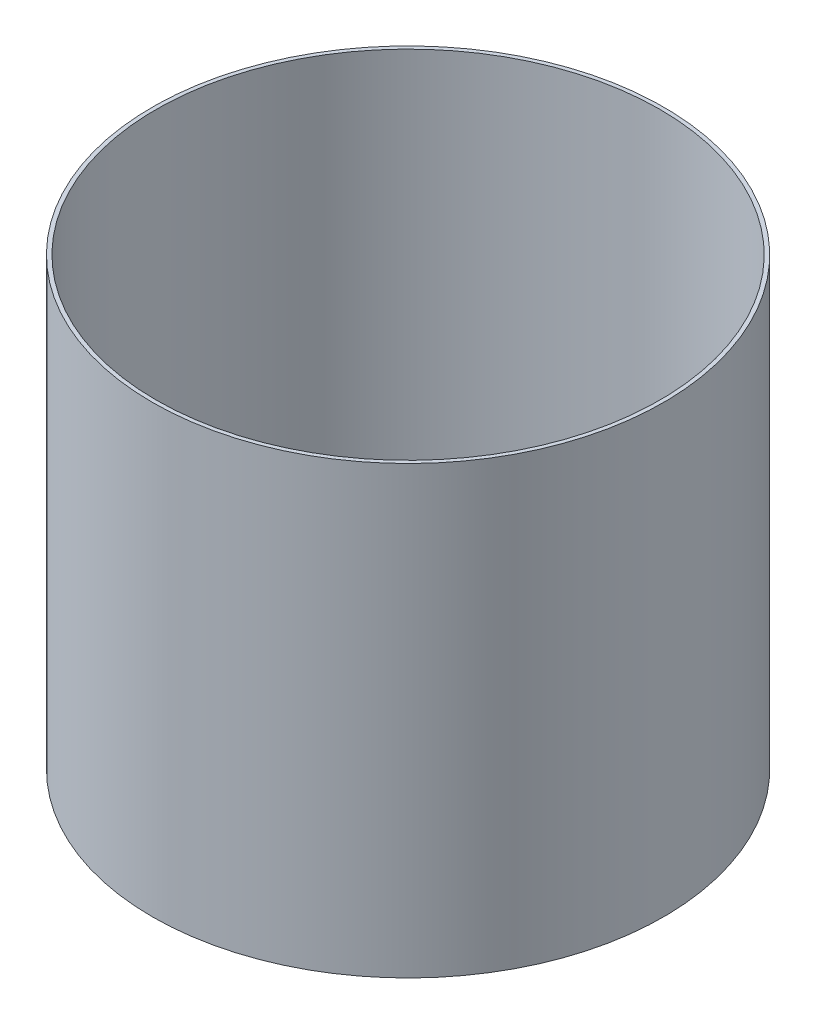
SolidWorks part; units mm, degrees
ref_plane "Front Plane" through (0, 0, 0) normal (0, 0, 1) x (1, 0, 0)
ref_plane "Top Plane" through (0, 0, 0) normal (0, 1, 0) x (1, 0, 0)
ref_plane "Right Plane" through (0, 0, 0) normal (1, 0, 0) x (0, 0, -1)
sketch "Sketch1" plane through (0, 0, 0) normal (0, 1, 0) x (1, 0, 0)
  circle A0 centre (0, 0) radius 335.28
extrude "Boss-Extrude2" add sketch "Sketch1" along normal blind 584.2
sketch "Sketch2" plane through (0, 584.2, 0) normal (0, 1, 0) x (1, 0, 0)
  circle A0 centre (0, 0) radius 330.2
extrude "Cut-Extrude2" cut sketch "Sketch2" against normal blind 558.8
